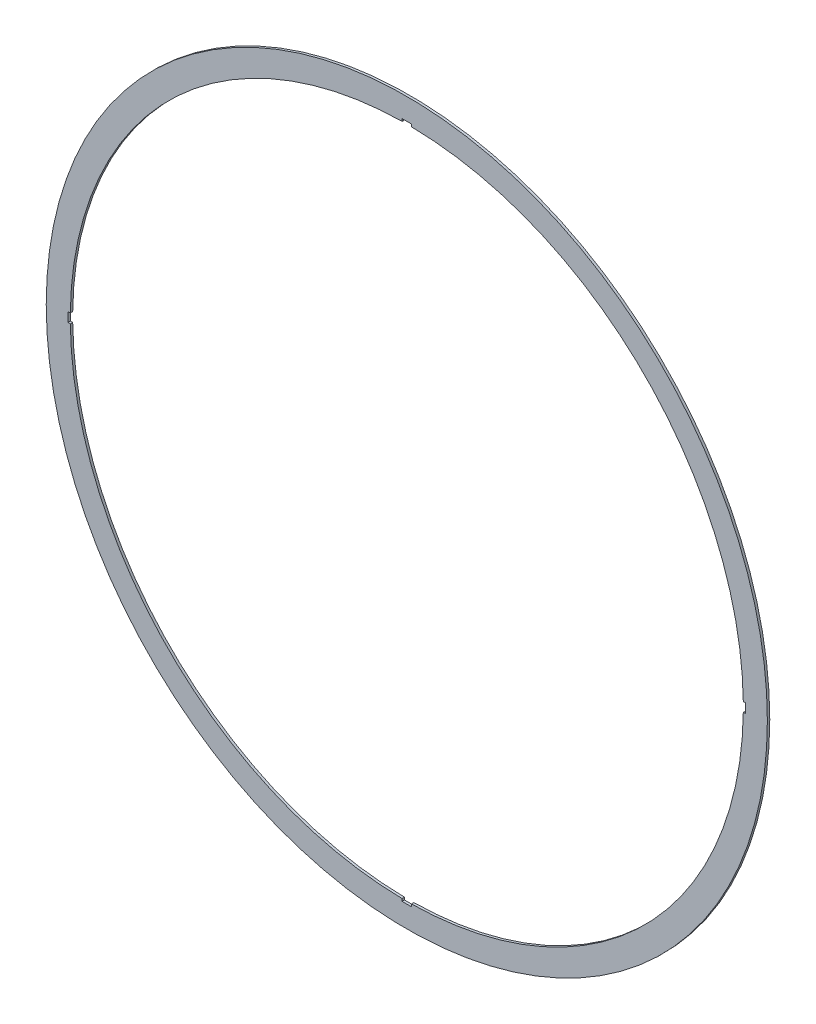
SolidWorks part; units mm, degrees
ref_plane "Front Plane" through (0, 0, 0) normal (0, 0, 1) x (1, 0, 0)
ref_plane "Top Plane" through (0, 0, 0) normal (0, 1, 0) x (1, 0, 0)
ref_plane "Right Plane" through (0, 0, 0) normal (1, 0, 0) x (0, 0, -1)
sketch "Sketch1" plane through (0, 0, 0) normal (0, 0, 1) x (1, 0, 0)
  line L0 (0, 0) -> (0, 484.7894) construction
  line L1 (423.001, 5.8605) -> (419.9591, 5.8605)
  line L2 (-5.8605, 423.001) -> (5.8605, 423.001)
  line L3 (-5.8605, 423.001) -> (-5.8605, 419.9591)
  line L5 (5.8605, 423.001) -> (5.8605, 419.9591)
  line L6 (-5.8605, 423.001) -> (0, 420) construction
  line L7 (0, 420) -> (5.8605, 423.001) construction
  line L8 (423.001, 5.8605) -> (423.001, -5.8605)
  line L9 (423.001, -5.8605) -> (419.9591, -5.8605)
  line L10 (5.8605, -423.001) -> (5.8605, -419.9591)
  line L11 (5.8605, -423.001) -> (-5.8605, -423.001)
  line L12 (-5.8605, -423.001) -> (-5.8605, -419.9591)
  line L13 (-423.001, -5.8605) -> (-419.9591, -5.8605)
  line L14 (-423.001, -5.8605) -> (-423.001, 5.8605)
  line L15 (-423.001, 5.8605) -> (-419.9591, 5.8605)
  circle A0 centre (0, 0) radius 450
  arc A1 (-5.8605, 419.9591) -> (-419.9591, 5.8605) centre (0, 0) ccw
  arc A2 (419.9591, 5.8605) -> (5.8605, 419.9591) centre (0, 0) ccw
  circle A3 centre (0, 0) radius 420 construction
  arc A4 (5.8605, -419.9591) -> (419.9591, -5.8605) centre (0, 0) ccw
  arc A5 (-419.9591, -5.8605) -> (-5.8605, -419.9591) centre (0, 0) ccw
  point P5 (0, 420)
  point P7 (430, 0)
  dimension "D1" = 30
  dimension "D3" = 900
  dimension "D2" = 4
extrude "Boss-Extrude1" add sketch "Sketch1" along normal blind 3
